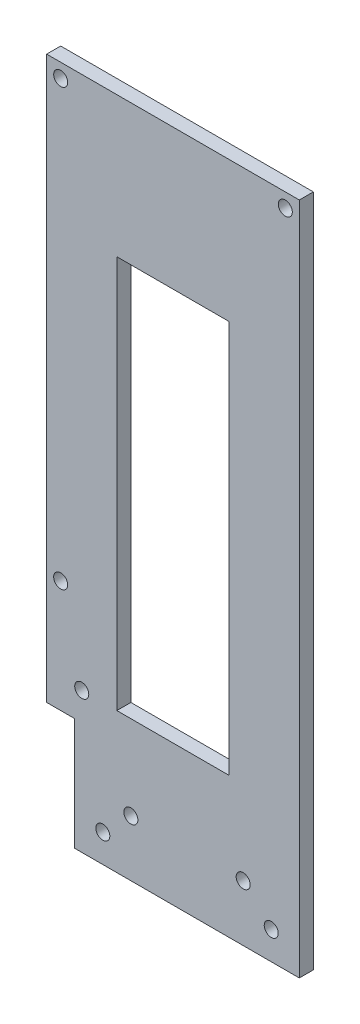
SolidWorks part; units mm, degrees
ref_plane "Front Plane" through (0, 0, 0) normal (0, 0, 1) x (1, 0, 0)
ref_plane "Top Plane" through (0, 0, 0) normal (0, 1, 0) x (1, 0, 0)
ref_plane "Right Plane" through (0, 0, 0) normal (1, 0, 0) x (0, 0, -1)
sketch "Sketch1" plane through (0, 0, 0) normal (0, 0, 1) x (1, 0, 0)
  line L0 (-90, -160) -> (-70, -160)
  line L1 (90, 240) -> (-90, 240)
  line L2 (90, 240) -> (90, -240)
  line L3 (90, -240) -> (-70, -240)
  line L4 (-90, 240) -> (-90, -160)
  line L5 (90, 240) -> (-70, -186.6667) construction
  line L6 (90, -240) -> (-90, 240) construction
  line L7 (-70, -160) -> (-70, -240)
  line L9 (40, -140) -> (-40, -140)
  line L10 (40, -140) -> (40, 140)
  line L11 (40, 140) -> (-40, 140)
  line L12 (-40, -140) -> (-40, 140)
  line L13 (40, -140) -> (-40, 140) construction
  line L14 (40, 140) -> (-40, -140) construction
  point P0 (0, 0)
  point P1 (0, 0)
  point P14 (0, -140)
  dimension "D1" = 180
  dimension "D2" = 100
  dimension "D3" = 80
  dimension "D4" = 20
  dimension "D5" = 50
  dimension "D6" = 50
  dimension "D7" = 100
extrude "Boss-Extrude1" add sketch "Sketch1" along normal blind 10
sketch "Sketch6" plane through (0, 0, 10) normal (0, 0, 1) x (1, 0, 0)
  line L0 (10, -240) -> (10, -140) construction
  line L1 (-70, -240) -> (90, -240) construction
  line L2 (-40, -140) -> (40, -140) construction
  line L3 (90, 240) -> (-90, 240) construction
  line L4 (-90, 240) -> (-90, -160) construction
  line L5 (90, -240) -> (90, 240) construction
  line L6 (-90, -160) -> (-70, -160) construction
  line L7 (-70, -160) -> (-70, -240) construction
  circle A0 centre (-50, -220) radius 5
  circle A1 centre (-30, -200) radius 5
  circle A2 centre (70, -220) radius 5
  circle A3 centre (50, -200) radius 5
  circle A4 centre (-80, 230) radius 5
  circle A5 centre (80, 230) radius 5
  circle A6 centre (-80, -80) radius 5
  circle A7 centre (-65, -140) radius 5
  dimension "D1" = 10
  dimension "D3" = 10
  dimension "D4" = 10
  dimension "D6" = 10
  dimension "D10" = 20
  dimension "D11" = 20
  dimension "D12" = 20
  dimension "D13" = 20
  dimension "D2" = 10
  dimension "D5" = 10
  dimension "D7" = 80
  dimension "D8" = 60
  dimension "D9" = 15
extrude "Cut-Extrude3" cut sketch "Sketch6" against normal blind 10
